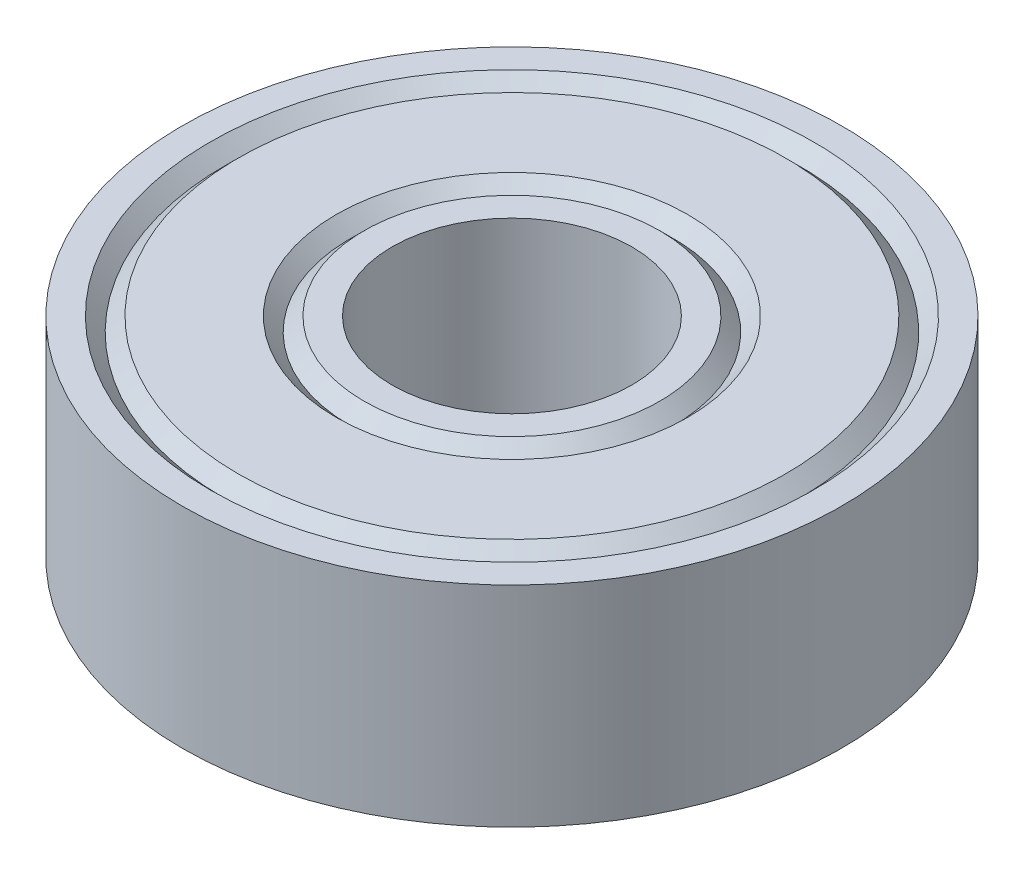
SolidWorks part; units mm, degrees
ref_plane "Front Plane" through (0, 0, 0) normal (0, 0, 1) x (1, 0, 0)
ref_plane "Top Plane" through (0, 0, 0) normal (0, 1, 0) x (1, 0, 0)
ref_plane "Right Plane" through (0, 0, 0) normal (1, 0, 0) x (0, 0, -1)
sketch "Sketch1" plane through (0, 0, 0) normal (0, 0, 1) x (1, 0, 0)
  line L0 (0, 3.5) -> (0, -3.5) construction
  line L1 (-4, 3.5) -> (-4.9333, 3.5)
  line L2 (-4, 3.5) -> (-4, -3.5)
  line L3 (-4, -3.5) -> (-4.9333, -3.5)
  line L4 (-11, 3.5) -> (-11, -3.5)
  line L5 (-10.0667, 3.5) -> (-9.6, 3.0333)
  line L6 (-9.6, 3.0333) -> (-9.1333, 3.5)
  line L7 (-5.8667, 3.5) -> (-5.4, 3.0333)
  line L8 (-5.4, 3.0333) -> (-4.9333, 3.5)
  line L9 (-10.0667, -3.5) -> (-9.6, -3.0333)
  line L10 (-9.6, -3.0333) -> (-9.1333, -3.5)
  line L11 (-5.8667, -3.5) -> (-5.4, -3.0333)
  line L12 (-5.4, -3.0333) -> (-4.9333, -3.5)
  line L13 (-5.8667, -3.5) -> (-9.1333, -3.5)
  line L14 (-10.0667, -3.5) -> (-11, -3.5)
  line L15 (-10.0667, 3.5) -> (-11, 3.5)
  line L16 (-5.8667, 3.5) -> (-9.1333, 3.5)
  line L17 (-9.6, 3.0333) -> (-5.4, 3.0333) construction
  line L18 (-9.6, 3.0333) -> (-9.6, -3.0333) construction
  line L19 (-5.4, -3.0333) -> (-9.6, -3.0333) construction
  line L20 (-5.4, 3.0333) -> (-5.4, -3.0333) construction
  line L21 (-9.6, 0) -> (-8.2, 0) construction
  line L22 (-4.9333, 3.5) -> (-5.8667, 3.5) construction
  line L23 (-8.2, 0) -> (-6.8, 0) construction
  line L24 (-9.6, 0) -> (-11, 0) construction
  line L25 (-6.8, 0) -> (-5.4, 0) construction
  line L26 (-5.4, 0) -> (-4, 0) construction
  dimension "D1" = 7
  dimension "D2" = 8
  dimension "D3" = 22
revolve "Revolve1" add sketch "Sketch1" angle 360 about L0
